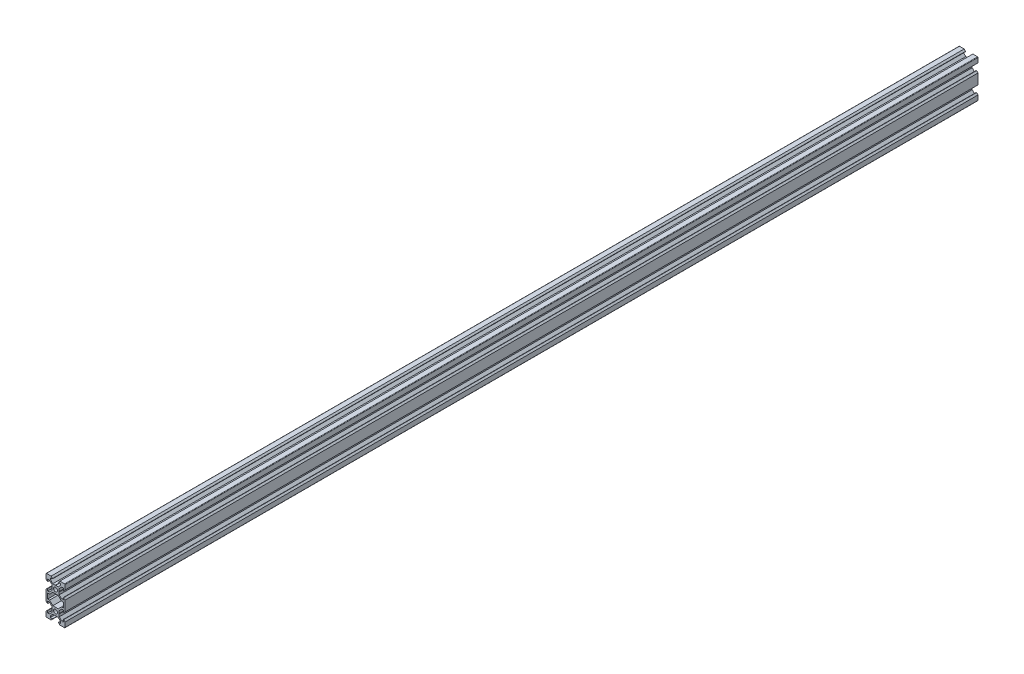
SolidWorks part; units mm, degrees
material "6063-T5"
ref_plane "Front Plane" through (0, 0, 0) normal (0, 0, 1) x (1, 0, 0)
ref_plane "Top Plane" through (0, 0, 0) normal (0, 1, 0) x (1, 0, 0)
ref_plane "Right Plane" through (0, 0, 0) normal (1, 0, 0) x (0, 0, -1)
ref_plane "Plane1" through (0, 0, 1000) normal (0, 0, 1) x (1, 0, 0)
sketch "Sketch1" plane through (0, 0, 1000) normal (0, 0, 1) x (1, 0, 0)
  line L0 (6.5607, 4.5) -> (3.9, 7.1607)
  line L1 (3.9, 7.1607) -> (3.9, 9.79)
  line L2 (3.9, 9.79) -> (3.69, 10)
  line L3 (3.69, 10) -> (3.9, 10.21)
  line L4 (3.9, 10.21) -> (3.9, 12.8393)
  line L5 (3.9, 12.8393) -> (6.5607, 15.5)
  line L6 (6.5607, 15.5) -> (8.2, 15.5)
  line L7 (8.2, 15.5) -> (8.2, 13.125)
  line L8 (8.2, 13.125) -> (8.545, 13.125)
  line L9 (8.545, 13.125) -> (10, 14.58)
  line L10 (10, 14.58) -> (10, 19.5)
  line L11 (9.5, 20) -> (4.58, 20)
  line L12 (4.58, 20) -> (3.125, 18.545)
  line L13 (3.125, 18.545) -> (3.125, 18.2)
  line L14 (3.125, 18.2) -> (5.5, 18.2)
  line L15 (5.5, 18.2) -> (5.5, 16.5607)
  line L16 (5.5, 16.5607) -> (2.8393, 13.9)
  line L17 (2.8393, 13.9) -> (0.21, 13.9)
  line L18 (0.21, 13.9) -> (0, 13.69)
  line L19 (0, 13.69) -> (-0.21, 13.9)
  line L20 (-0.21, 13.9) -> (-2.8393, 13.9)
  line L21 (-2.8393, 13.9) -> (-5.5, 16.5607)
  line L22 (-5.5, 16.5607) -> (-5.5, 18.2)
  line L23 (-5.5, 18.2) -> (-3.125, 18.2)
  line L24 (-3.125, 18.2) -> (-3.125, 18.545)
  line L25 (-3.125, 18.545) -> (-4.58, 20)
  line L26 (-4.58, 20) -> (-9.5, 20)
  line L27 (-10, 19.5) -> (-10, 14.58)
  line L28 (-10, 14.58) -> (-8.545, 13.125)
  line L29 (-8.545, 13.125) -> (-8.2, 13.125)
  line L30 (-8.2, 13.125) -> (-8.2, 15.5)
  line L31 (-8.2, 15.5) -> (-6.5607, 15.5)
  line L32 (-6.5607, 15.5) -> (-3.9, 12.8393)
  line L33 (-3.9, 12.8393) -> (-3.9, 10.21)
  line L34 (-3.9, 10.21) -> (-3.69, 10)
  line L35 (-3.69, 10) -> (-3.9, 9.79)
  line L36 (-3.9, 9.79) -> (-3.9, 7.1607)
  line L37 (-3.9, 7.1607) -> (-6.5607, 4.5)
  line L38 (-6.5607, 4.5) -> (-8.2, 4.5)
  line L39 (-8.2, 4.5) -> (-8.2, 6.875)
  line L40 (-8.2, 6.875) -> (-8.545, 6.875)
  line L41 (-8.545, 6.875) -> (-10, 5.42)
  line L42 (-10, 5.42) -> (-10, -5.42)
  line L43 (-10, -5.42) -> (-8.545, -6.875)
  line L44 (-8.545, -6.875) -> (-8.2, -6.875)
  line L45 (-8.2, -6.875) -> (-8.2, -4.5)
  line L46 (-8.2, -4.5) -> (-6.5607, -4.5)
  line L47 (-6.5607, -4.5) -> (-3.9, -7.1607)
  line L48 (-3.9, -7.1607) -> (-3.9, -9.79)
  line L49 (-3.9, -9.79) -> (-3.69, -10)
  line L50 (-3.69, -10) -> (-3.9, -10.21)
  line L51 (-3.9, -10.21) -> (-3.9, -12.8393)
  line L52 (-3.9, -12.8393) -> (-6.5607, -15.5)
  line L53 (-6.5607, -15.5) -> (-8.2, -15.5)
  line L54 (-8.2, -15.5) -> (-8.2, -13.125)
  line L55 (-8.2, -13.125) -> (-8.545, -13.125)
  line L56 (-8.545, -13.125) -> (-10, -14.58)
  line L57 (-10, -14.58) -> (-10, -19.5)
  line L58 (-9.5, -20) -> (-4.58, -20)
  line L59 (-4.58, -20) -> (-3.125, -18.545)
  line L60 (-3.125, -18.545) -> (-3.125, -18.2)
  line L61 (-3.125, -18.2) -> (-5.5, -18.2)
  line L62 (-5.5, -18.2) -> (-5.5, -16.5607)
  line L63 (-5.5, -16.5607) -> (-2.8393, -13.9)
  line L64 (-2.8393, -13.9) -> (-0.21, -13.9)
  line L65 (-0.21, -13.9) -> (0, -13.69)
  line L66 (0, -13.69) -> (0.21, -13.9)
  line L67 (0.21, -13.9) -> (2.8393, -13.9)
  line L68 (2.8393, -13.9) -> (5.5, -16.5607)
  line L69 (5.5, -16.5607) -> (5.5, -18.2)
  line L70 (5.5, -18.2) -> (3.125, -18.2)
  line L71 (3.125, -18.2) -> (3.125, -18.545)
  line L72 (3.125, -18.545) -> (4.58, -20)
  line L73 (4.58, -20) -> (9.5, -20)
  line L74 (10, -19.5) -> (10, -14.58)
  line L75 (10, -14.58) -> (8.545, -13.125)
  line L76 (8.545, -13.125) -> (8.2, -13.125)
  line L77 (8.2, -13.125) -> (8.2, -15.5)
  line L78 (8.2, -15.5) -> (6.5607, -15.5)
  line L79 (6.5607, -15.5) -> (3.9, -12.8393)
  line L80 (3.9, -12.8393) -> (3.9, -10.21)
  line L81 (3.9, -10.21) -> (3.69, -10)
  line L82 (3.69, -10) -> (3.9, -9.79)
  line L83 (3.9, -9.79) -> (3.9, -7.1607)
  line L84 (3.9, -7.1607) -> (6.5607, -4.5)
  line L85 (6.5607, -4.5) -> (8.2, -4.5)
  line L86 (8.2, -4.5) -> (8.2, -6.875)
  line L87 (8.2, -6.875) -> (8.545, -6.875)
  line L88 (8.545, -6.875) -> (10, -5.42)
  line L89 (10, -5.42) -> (10, 5.42)
  line L90 (10, 5.42) -> (8.545, 6.875)
  line L91 (8.545, 6.875) -> (8.2, 6.875)
  line L92 (8.2, 6.875) -> (8.2, 4.5)
  line L93 (8.2, 4.5) -> (6.5607, 4.5)
  line L94 (2.8393, -6.1) -> (-2.8393, -6.1)
  line L95 (-2.8393, -6.1) -> (-6.2393, -2.7)
  line L96 (-6.2393, -2.7) -> (-8.2, -2.7)
  line L97 (-8.2, -2.7) -> (-8.2, 2.7)
  line L98 (-8.2, 2.7) -> (-6.2393, 2.7)
  line L99 (-6.2393, 2.7) -> (-2.8393, 6.1)
  line L100 (-2.8393, 6.1) -> (2.8393, 6.1)
  line L101 (2.8393, 6.1) -> (6.2393, 2.7)
  line L102 (6.2393, 2.7) -> (8.2, 2.7)
  line L103 (8.2, 2.7) -> (8.2, -2.7)
  line L104 (8.2, -2.7) -> (6.2393, -2.7)
  line L105 (6.2393, -2.7) -> (2.8393, -6.1)
  circle A0 centre (0, 10) radius 2.1
  circle A1 centre (0, -10) radius 2.1
  arc A2 (10, 19.5) -> (9.5, 20) centre (9.5, 19.5) ccw
  arc A3 (-9.5, 20) -> (-10, 19.5) centre (-9.5, 19.5) ccw
  arc A4 (-10, -19.5) -> (-9.5, -20) centre (-9.5, -19.5) ccw
  arc A5 (9.5, -20) -> (10, -19.5) centre (9.5, -19.5) ccw
  dimension "D1" = 0.5
  dimension "D3" = 4.2
  dimension "D2" = 7.8
extrude "Boss-Extrude1" add sketch "Sketch1" against normal blind 960
